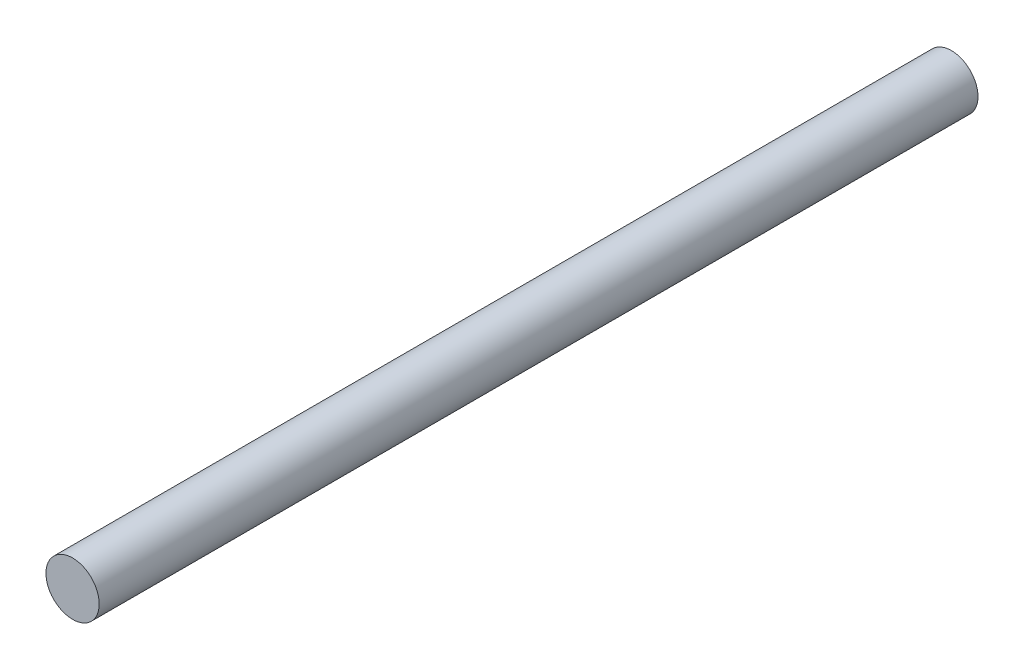
SolidWorks part; units mm, degrees
material "201 Annealed Stainless Steel (SS)"
ref_plane "Front Plane" through (0, 0, 0) normal (0, 0, 1) x (1, 0, 0)
ref_plane "Top Plane" through (0, 0, 0) normal (0, 1, 0) x (1, 0, 0)
ref_plane "Right Plane" through (0, 0, 0) normal (1, 0, 0) x (0, 0, -1)
sketch "Sketch1" plane through (0, 0, 0) normal (0, 0, 1) x (1, 0, 0)
  circle A0 centre (0, 0) radius 2
  dimension "D1" = 4
extrude "Boss-Extrude1" add sketch "Sketch1" along normal mid plane 66 contours A0
cosmetic thread "Cosmetic Thread1" parameters "D1"=14, "D2"=3.22
cosmetic thread "Cosmetic Thread2" parameters "D1"=7, "D2"=3.22
